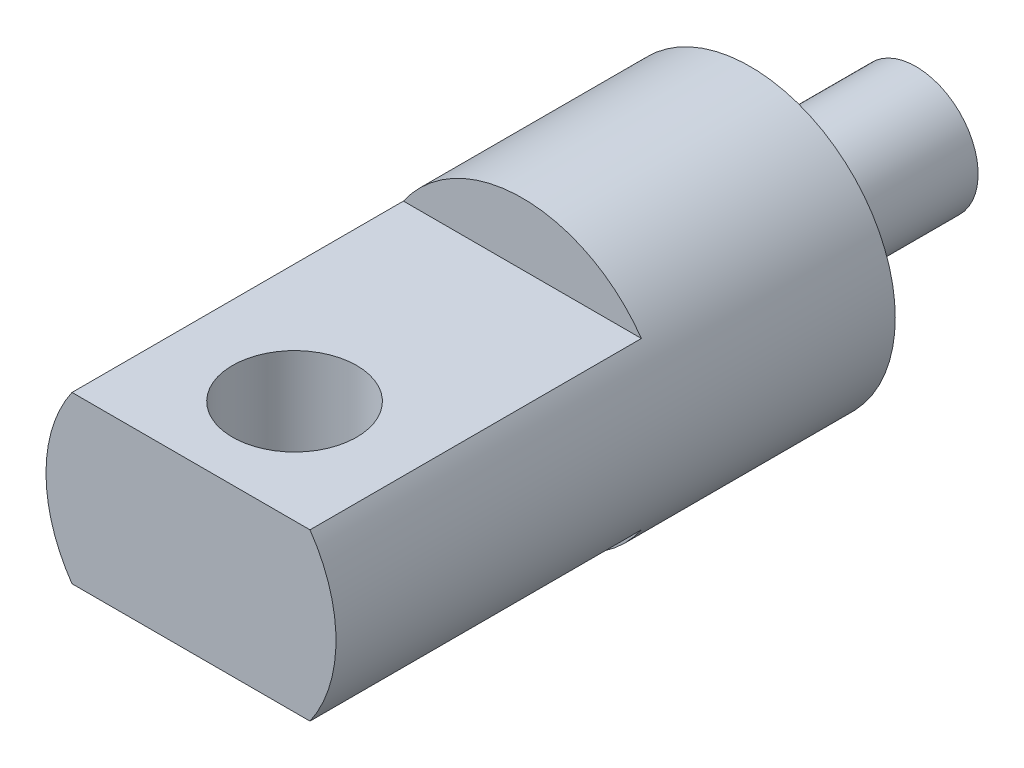
SolidWorks part; units mm, degrees
ref_plane "Front Plane" through (0, 0, 0) normal (0, 0, 1) x (1, 0, 0)
ref_plane "Top Plane" through (0, 0, 0) normal (0, 1, 0) x (1, 0, 0)
ref_plane "Right Plane" through (0, 0, 0) normal (1, 0, 0) x (0, 0, -1)
sketch "Sketch3" plane through (0, 0, 0) normal (0, 0, 1) x (1, 0, 0)
  circle A0 centre (0, 0) radius 35
  dimension "D1" = 70
extrude "Boss-Extrude2" add sketch "Sketch3" against normal blind 150 and the other way blind 25
sketch "Sketch4" plane through (0, 0, -150) normal (0, 0, -1) x (-1, 0, 0)
  circle A0 centre (0, 0) radius 15
  circle A1 centre (0, 0) radius 35
  circle A2 centre (0, 0) radius 35 construction
  dimension "D1" = 30
extrude "Cut-Extrude1" cut sketch "Sketch4" against normal blind 40
sketch "Sketch5" plane through (0, 0, 25) normal (0, 0, 1) x (1, 0, 0)
  line L0 (-28.7228, 20) -> (28.7228, 20)
  line L1 (-28.7228, -20) -> (28.7228, -20)
  line L2 (0, -20) -> (0, 0) construction
  line L3 (0, 0) -> (0, 20) construction
  arc A0 (-28.7228, 20) -> (-28.7228, -20) centre (0, 0) ccw construction
  circle A1 centre (0, 0) radius 35
  arc A2 (-28.7228, -20) -> (28.7228, -20) centre (0, 0) ccw
  arc A3 (28.7228, 20) -> (-28.7228, 20) centre (0, 0) ccw
  arc A4 (28.7228, -20) -> (28.7228, 20) centre (0, 0) ccw construction
  dimension "D2" = 40
  dimension "D1" = 0
extrude "Cut-Extrude2" cut sketch "Sketch5" against normal blind 80
sketch "Sketch7" plane through (0, -20, 0) normal (0, -1, 0) x (1, 0, 0)
  circle A0 centre (0, 0) radius 15
  dimension "D1" = 30
extrude "Cut-Extrude3" cut sketch "Sketch7" against normal through all
